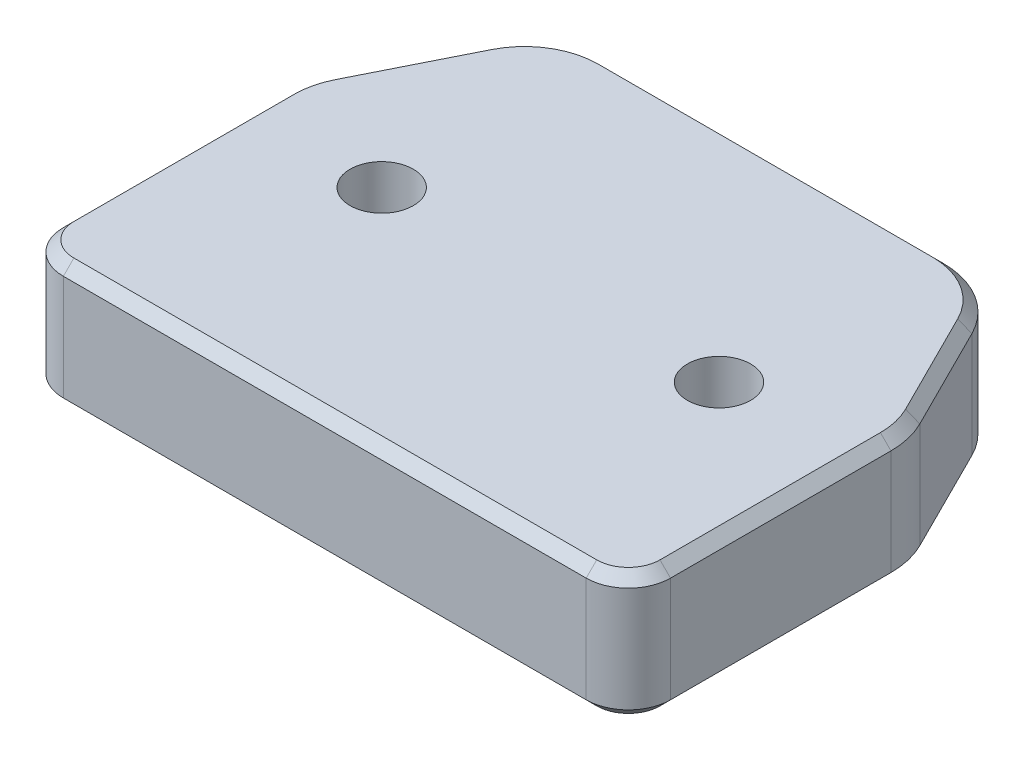
SolidWorks part; units mm, degrees
ref_plane "Front Plane" through (0, 0, 0) normal (0, 0, 1) x (1, 0, 0)
ref_plane "Top Plane" through (0, 0, 0) normal (0, 1, 0) x (1, 0, 0)
ref_plane "Right Plane" through (0, 0, 0) normal (1, 0, 0) x (0, 0, -1)
sketch "Sketch1" plane through (0, 0, 0) normal (0, 1, 0) x (1, 0, 0)
  line L0 (-14.4, 2.7) -> (-10.4, 10.7)
  line L1 (-14.4, -10.7) -> (14.4, -10.7)
  line L2 (-14.4, -10.7) -> (-14.4, 10.7)
  line L3 (-14.4, 10.7) -> (14.4, 10.7)
  line L4 (14.4, -10.7) -> (14.4, 10.7)
  line L5 (-14.4, -10.7) -> (14.4, 10.7) construction
  line L6 (-14.4, 10.7) -> (14.4, -10.7) construction
  line L7 (10.4, 10.7) -> (14.4, 2.7)
  point P0 (0, 0)
  point P10 (0, 0)
  dimension "D1" = 28.8
  dimension "D2" = 21.4
  dimension "D3" = 8
  dimension "D4" = 4
  dimension "D5" = 4
extrude "Boss-Extrude1" add sketch "Sketch1" along normal blind 6 contours L7 L3 L0 L2 L1 L4
fillet "Fillet1" radius 4 4 edges at (-14.4, 3, -2.7) (14.4, 3, -2.7) (-10.4, 3, -10.7) (10.4, 3, -10.7)
fillet "Fillet2" radius 2 2 edges at (14.4, 3, 10.7) (-14.4, 3, 10.7)
sketch "Sketch2" plane through (0, 0, 0) normal (0, -1, 0) x (1, 0, 0)
  circle A0 centre (-8, 0) radius 1.5
  circle A1 centre (8, 0) radius 1.5
  point P4 (0, 0)
  dimension "D1" = 3
  dimension "D2" = 8
  dimension "D3" = 8
extrude "Cut-Extrude1" cut sketch "Sketch2" against normal blind 6
chamfer "Chamfer1" distance 0.5 angle 45 24 edges at (-12.7416, 0, -6.0167) (-14.293, 0, -2.6747) (-10.0308, 0, -10.1026) (-14.4, 0, 3.4721) (0, 0, -10.7) (-13.8142, 0, 10.1142) (10.0308, 0, -10.1026) (0, 0, 10.7) (12.7416, 0, -6.0167) (13.8142, 0, 10.1142) (14.293, 0, -2.6747) (14.4, 0, 3.4721) (-12.7416, 6, -6.0167) (-14.293, 6, -2.6747) (-10.0308, 6, -10.1026) (-14.4, 6, 3.4721) (0, 6, -10.7) (-13.8142, 6, 10.1142) (10.0308, 6, -10.1026) (0, 6, 10.7) (12.7416, 6, -6.0167) (13.8142, 6, 10.1142) (14.293, 6, -2.6747) (14.4, 6, 3.4721)
